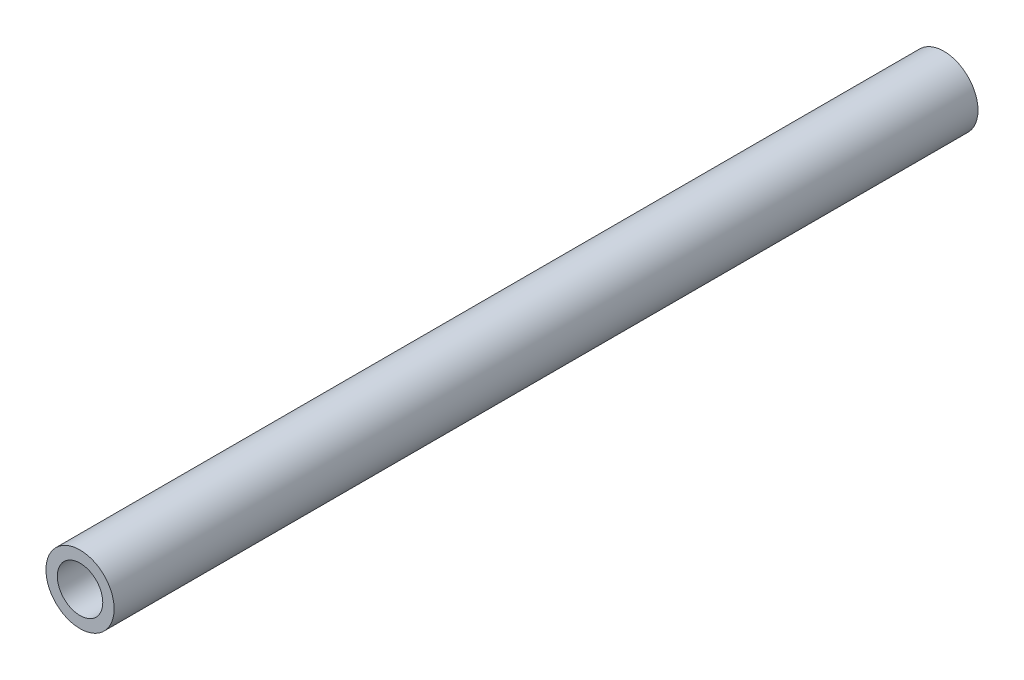
SolidWorks part; units mm, degrees
ref_plane "前视基准面" through (0, 0, 0) normal (0, 0, 1) x (1, 0, 0)
ref_plane "上视基准面" through (0, 0, 0) normal (0, 1, 0) x (1, 0, 0)
ref_plane "右视基准面" through (0, 0, 0) normal (1, 0, 0) x (0, 0, -1)
sketch "Sketch1" plane through (0, 0, 0) normal (0, 0, 1) x (1, 0, 0)
  circle A0 centre (0, 0) radius 1.5
  circle A1 centre (0, 0) radius 1
  dimension "D1" = 3
  dimension "D2" = 2
extrude "Boss-Extrude1" add sketch "Sketch1" along normal blind 38
